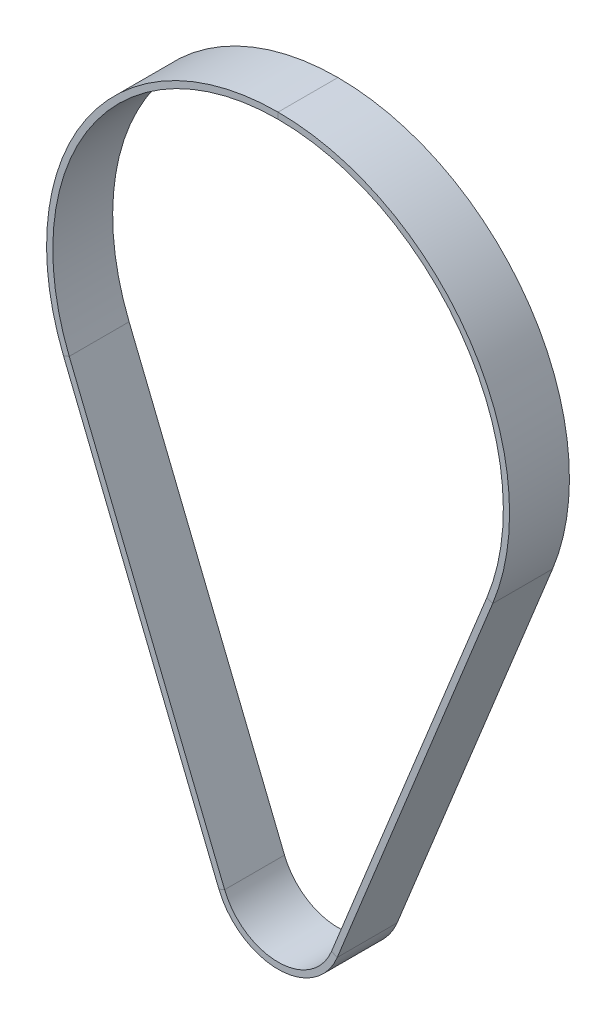
SolidWorks part; units mm, degrees
ref_plane "Спереди" through (0, 0, 0) normal (0, 0, 1) x (1, 0, 0)
ref_plane "Сверху" through (0, 0, 0) normal (0, 1, 0) x (1, 0, 0)
ref_plane "Справа" through (0, 0, 0) normal (1, 0, 0) x (0, 0, -1)
other "Configuration Table"
sketch "Эскиз1" plane through (0, 0, 0) normal (0, 0, 1) x (1, 0, 0)
  line L0 (-53.7674, -21.75) -> (-14.8324, -118)
  line L2 (14.8324, -118) -> (53.7674, -21.75)
  arc A0 (53.7674, -21.75) -> (-53.7674, -21.75) centre (0, 0) ccw
  arc A1 (-14.8324, -118) -> (14.8324, -118) centre (0, -112) ccw
  dimension "D1" = 116
  dimension "D2" = 32
  dimension "D3" = 112
sketch "Эскиз2" plane through (0, 0, 0) normal (1, 0, 0) x (0, 0, -1)
  line L0 (0, 58) -> (0, -21.75) construction
  line L1 (-15, 58) -> (0, 58)
  line L2 (-15, 58) -> (-15, 56.44)
  line L3 (-15, 56.44) -> (0, 56.44)
  line L4 (0, 58) -> (0, 56.44)
  dimension "D1" = 1.56
  dimension "D2" = 15
  dimension "D3" = 58
sweep "По траектории1" add profiles "Эскиз2" path "Эскиз1"
